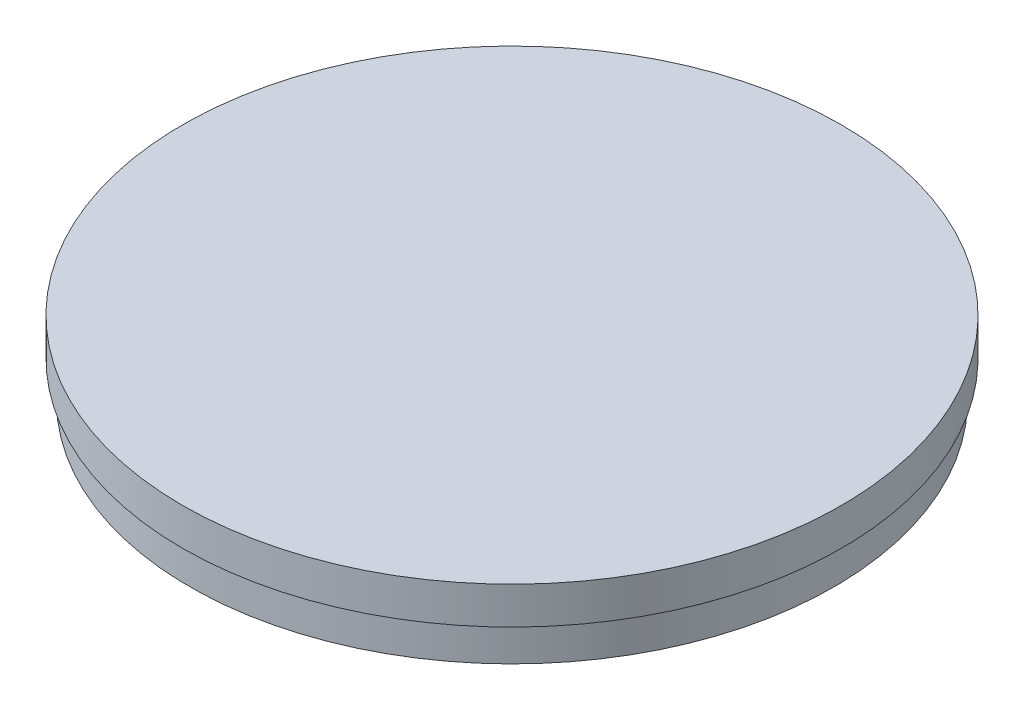
SolidWorks part; units mm, degrees
ref_plane "Front Plane" through (0, 0, 0) normal (0, 0, 1) x (1, 0, 0)
ref_plane "Top Plane" through (0, 0, 0) normal (0, 1, 0) x (1, 0, 0)
ref_plane "Right Plane" through (0, 0, 0) normal (1, 0, 0) x (0, 0, -1)
sketch "Sketch1" plane through (0, 0, 0) normal (0, 0, 1) x (1, 0, 0)
  line L0 (0, 0) -> (0, 11.938)
  line L1 (0, 11.938) -> (52.959, 11.938)
  line L2 (52.959, 11.938) -> (52.959, 5.969)
  line L3 (0, 0) -> (51.7652, 0)
  line L4 (52.959, 5.969) -> (51.7652, 5.969)
  line L5 (51.7652, 5.969) -> (51.7652, 0)
  dimension "D1" = 52.959
  dimension "D2" = 11.938
  dimension "D3" = 1.1938
  dimension "D4" = 5.969
revolve "Revolve1" add sketch "Sketch1" angle 360 about L0
